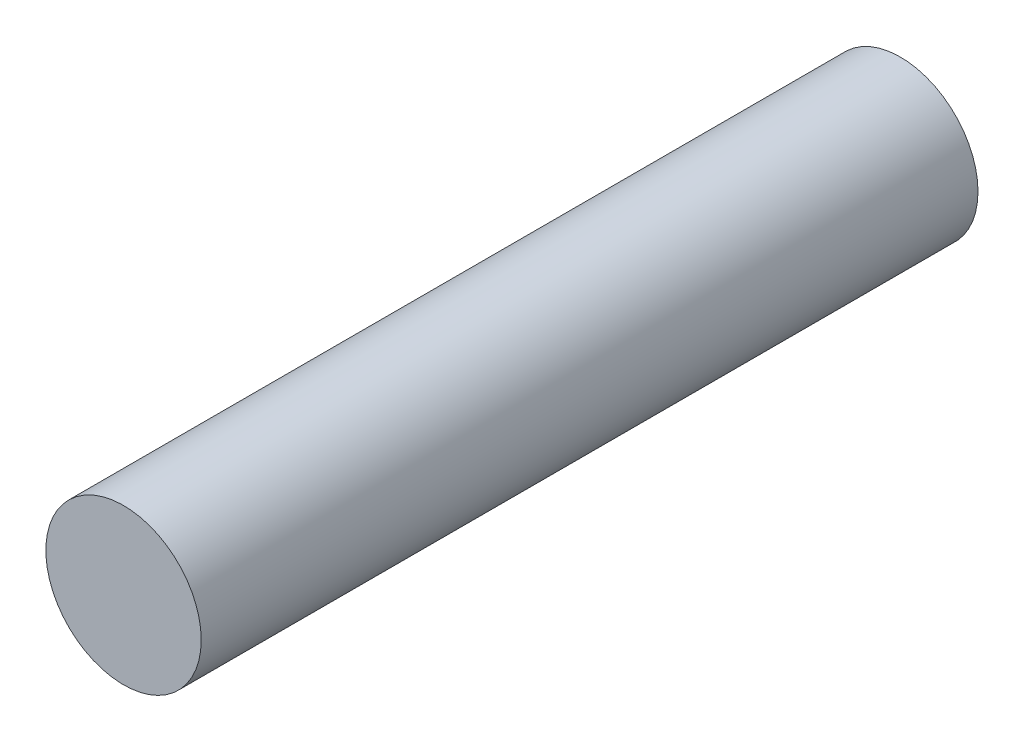
SolidWorks part; units mm, degrees
ref_plane "Front Plane" through (0, 0, 0) normal (0, 0, 1) x (1, 0, 0)
ref_plane "Top Plane" through (0, 0, 0) normal (0, 1, 0) x (1, 0, 0)
ref_plane "Right Plane" through (0, 0, 0) normal (1, 0, 0) x (0, 0, -1)
sketch "S01 - M6 connecting stud" plane through (0, 0, 0) normal (0, 0, 1) x (1, 0, 0)
  circle A0 centre (0, 0) radius 3
extrude "01 - M6 connecting stud" add sketch "S01 - M6 connecting stud" along normal blind 30
sketch "S02 - Hex key socket" plane through (0, 0, 0) normal (0, 0, 1) x (1, 0, 0)
  line L0 (1.7321, 0) -> (0.866, 1.5)
  line L1 (0.866, 1.5) -> (-0.866, 1.5)
  line L2 (-0.866, 1.5) -> (-1.7321, 0)
  line L3 (-1.7321, 0) -> (-0.866, -1.5)
  line L4 (-0.866, -1.5) -> (0.866, -1.5)
  line L5 (0.866, -1.5) -> (1.7321, 0)
extrude "02 - Hex key socket" cut sketch "S02 - Hex key socket" along normal blind 3.1 from offset 0.1
